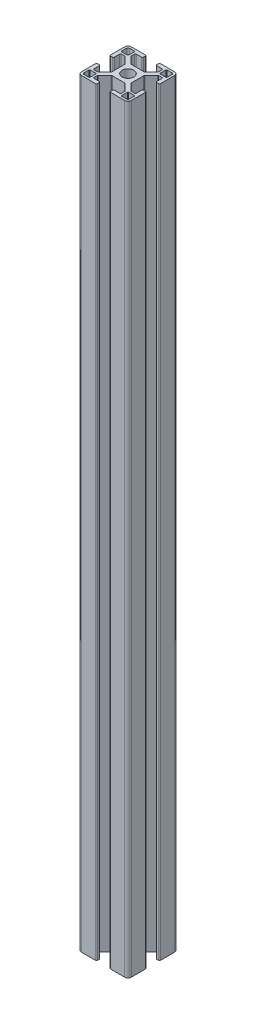
SolidWorks part; units mm, degrees
ref_plane "Front Plane" through (0, 0, 0) normal (0, 0, 1) x (1, 0, 0)
ref_plane "Top Plane" through (0, 0, 0) normal (0, 1, 0) x (1, 0, 0)
ref_plane "Right Plane" through (0, 0, 0) normal (1, 0, 0) x (0, 0, -1)
sketch "Sketch1" plane through (0, 0, 0) normal (0, 1, 0) x (1, 0, 0)
  line L0 (3.9799, -2.4733) -> (3.1981, -1.4942) construction
  line L1 (1.4942, -3.1981) -> (2.4733, -3.9799) construction
  line L2 (-2.4733, -3.9799) -> (-1.4942, -3.1981) construction
  line L3 (-3.1981, -1.4942) -> (-3.9799, -2.4733) construction
  line L4 (-3.9799, 2.4733) -> (-3.1981, 1.4942) construction
  line L5 (-1.4942, 3.1981) -> (-2.4733, 3.9799) construction
  line L6 (2.4733, 3.9799) -> (1.4942, 3.1981) construction
  line L7 (3.1981, 1.4942) -> (3.9799, 2.4733) construction
  line L8 (-12.6999, -13.6999) -> (-9.881, -13.6999)
  line L9 (-13.6999, -9.881) -> (-13.6999, -12.6999)
  line L10 (-9.88, -9.5) -> (-13.3189, -9.5)
  line L11 (-9.5, -13.3189) -> (-9.5, -9.88)
  line L12 (13.6999, -12.6999) -> (13.6999, -9.881)
  line L13 (9.881, -13.6999) -> (12.6999, -13.6999)
  line L14 (9.5, -9.88) -> (9.5, -13.3189)
  line L15 (13.3189, -9.5) -> (9.88, -9.5)
  line L16 (9.88, 9.5) -> (13.3189, 9.5)
  line L17 (9.5, 13.3189) -> (9.5, 9.88)
  line L18 (12.6999, 13.6999) -> (9.881, 13.6999)
  line L19 (13.6999, 9.881) -> (13.6999, 12.6999)
  line L20 (-13.6999, 12.6999) -> (-13.6999, 9.881)
  line L21 (-9.881, 13.6999) -> (-12.6999, 13.6999)
  line L22 (-9.5, 9.88) -> (-9.5, 13.3189)
  line L23 (-13.3189, 9.5) -> (-9.88, 9.5)
  line L24 (14.4999, -4) -> (13.2425, -4)
  line L25 (12.7425, -4.5) -> (12.7425, -7.7325)
  line L26 (12.2428, -8.25) -> (10.2602, -8.25)
  line L27 (9.9066, -8.1035) -> (5.9811, -4.178)
  line L28 (5.8347, -3.8245) -> (5.8347, -1.0125)
  line L29 (5.8347, -1.0125) -> (5.3247, -0.0625) construction
  line L30 (5.3247, -0.0625) -> (5.8347, 0.8875) construction
  line L31 (5.8347, 0.8875) -> (5.8347, 3.8245)
  line L32 (5.9811, 4.178) -> (9.9066, 8.1035)
  line L33 (10.2602, 8.25) -> (12.2428, 8.25)
  line L34 (12.7425, 7.7325) -> (12.7425, 4.5)
  line L35 (13.2425, 4) -> (14.4999, 4)
  line L36 (14.9999, 4.5) -> (14.9999, 12.9999)
  line L37 (12.9999, 14.9999) -> (4.5, 14.9999)
  line L38 (4, 14.4999) -> (4, 13.2425)
  line L39 (4.5, 12.7425) -> (7.7325, 12.7425)
  line L40 (8.25, 12.2428) -> (8.25, 10.2602)
  line L41 (8.1035, 9.9066) -> (4.178, 5.9811)
  line L42 (3.8245, 5.8347) -> (0.95, 5.8347)
  line L43 (0.95, 5.8347) -> (0, 5.3247) construction
  line L44 (0, 5.3247) -> (-0.95, 5.8347) construction
  line L45 (-0.95, 5.8347) -> (-3.8245, 5.8347)
  line L46 (-4.178, 5.9811) -> (-8.1035, 9.9066)
  line L47 (-8.25, 10.2602) -> (-8.25, 12.2428)
  line L48 (-7.7325, 12.7425) -> (-4.5, 12.7425)
  line L49 (-4, 13.2425) -> (-4, 14.4999)
  line L50 (-4.5, 14.9999) -> (-12.9999, 14.9999)
  line L51 (-14.9999, 12.9999) -> (-14.9999, 4.5)
  line L52 (-14.4999, 4) -> (-13.2425, 4)
  line L53 (-12.7425, 4.5) -> (-12.7425, 7.7325)
  line L54 (-12.2428, 8.25) -> (-10.2602, 8.25)
  line L55 (-9.9066, 8.1035) -> (-5.9811, 4.178)
  line L56 (-5.8347, 3.8245) -> (-5.8347, 0.8875)
  line L57 (-5.8347, 0.8875) -> (-5.3247, -0.0625) construction
  line L58 (-5.3247, -0.0625) -> (-5.8347, -1.0125) construction
  line L59 (-5.8347, -1.0125) -> (-5.8347, -3.8245)
  line L60 (-5.9811, -4.178) -> (-9.9066, -8.1035)
  line L61 (-10.2602, -8.25) -> (-12.2428, -8.25)
  line L62 (-12.7425, -7.7325) -> (-12.7425, -4.5)
  line L63 (-13.2425, -4) -> (-14.4999, -4)
  line L64 (-14.9999, -4.5) -> (-14.9999, -12.9999)
  line L65 (-12.9999, -14.9999) -> (-4.5, -14.9999)
  line L66 (-4, -14.4999) -> (-4, -13.2425)
  line L67 (-4.5, -12.7425) -> (-7.7325, -12.7425)
  line L68 (-8.25, -12.2428) -> (-8.25, -10.2602)
  line L69 (-8.1035, -9.9066) -> (-4.178, -5.9811)
  line L70 (-3.8245, -5.8347) -> (-0.95, -5.8347)
  line L71 (-0.95, -5.8347) -> (0, -5.3247) construction
  line L72 (0, -5.3247) -> (0.95, -5.8347) construction
  line L73 (0.95, -5.8347) -> (3.8245, -5.8347)
  line L74 (4.178, -5.9811) -> (8.1035, -9.9066)
  line L75 (8.25, -10.2602) -> (8.25, -12.2428)
  line L76 (7.7325, -12.7425) -> (4.5, -12.7425)
  line L77 (4, -13.2425) -> (4, -14.4999)
  line L78 (4.5, -14.9999) -> (12.9999, -14.9999)
  line L79 (14.9999, -12.9999) -> (14.9999, -4.5)
  line L80 (-5.8347, -1.0125) -> (-5.8347, 0.8875)
  line L81 (-0.95, 5.8347) -> (0.95, 5.8347)
  line L82 (5.8347, 0.8875) -> (5.8347, -1.0125)
  line L83 (-0.95, -5.8347) -> (0.95, -5.8347)
  arc A0 (2.4733, -3.9799) -> (3.9799, -2.4733) centre (3.1422, -3.1422) ccw construction
  arc A1 (-1.4942, -3.1981) -> (1.4942, -3.1981) centre (0, 0) ccw construction
  arc A2 (-3.9799, -2.4733) -> (-2.4733, -3.9799) centre (-3.1422, -3.1422) ccw construction
  arc A3 (-3.1981, 1.4942) -> (-3.1981, -1.4942) centre (0, 0) ccw construction
  arc A4 (-2.4733, 3.9799) -> (-3.9799, 2.4733) centre (-3.1422, 3.1422) ccw construction
  arc A5 (1.4942, 3.1981) -> (-1.4942, 3.1981) centre (0, 0) ccw construction
  arc A6 (3.9799, 2.4733) -> (2.4733, 3.9799) centre (3.1422, 3.1422) ccw construction
  arc A7 (3.1981, -1.4942) -> (3.1981, 1.4942) centre (0, 0) ccw construction
  arc A8 (-13.6999, -12.6999) -> (-12.6999, -13.6999) centre (-12.6999, -12.6999) ccw
  arc A9 (-13.3189, -9.5) -> (-13.6999, -9.881) centre (-13.3189, -9.881) ccw
  arc A10 (-9.5, -9.88) -> (-9.88, -9.5) centre (-9.88, -9.88) ccw
  arc A11 (-9.881, -13.6999) -> (-9.5, -13.3189) centre (-9.881, -13.3189) ccw
  arc A12 (12.6999, -13.6999) -> (13.6999, -12.6999) centre (12.6999, -12.6999) ccw
  arc A13 (9.5, -13.3189) -> (9.881, -13.6999) centre (9.881, -13.3189) ccw
  arc A14 (9.88, -9.5) -> (9.5, -9.88) centre (9.88, -9.88) ccw
  arc A15 (13.6999, -9.881) -> (13.3189, -9.5) centre (13.3189, -9.881) ccw
  arc A16 (9.5, 9.88) -> (9.88, 9.5) centre (9.88, 9.88) ccw
  arc A17 (9.881, 13.6999) -> (9.5, 13.3189) centre (9.881, 13.3189) ccw
  arc A18 (13.6999, 12.6999) -> (12.6999, 13.6999) centre (12.6999, 12.6999) ccw
  arc A19 (13.3189, 9.5) -> (13.6999, 9.881) centre (13.3189, 9.881) ccw
  arc A20 (14.9999, -4.5) -> (14.4999, -4) centre (14.4999, -4.5) ccw
  arc A21 (13.2425, -4) -> (12.7425, -4.5) centre (13.2425, -4.5) ccw
  arc A22 (12.2428, -8.25) -> (12.7425, -7.7325) centre (12.2428, -7.75) ccw
  arc A23 (9.9066, -8.1035) -> (10.2602, -8.25) centre (10.2602, -7.75) ccw
  arc A24 (5.8347, -3.8245) -> (5.9811, -4.178) centre (6.3347, -3.8245) ccw
  arc A25 (5.9811, 4.178) -> (5.8347, 3.8245) centre (6.3347, 3.8245) ccw
  arc A26 (10.2602, 8.25) -> (9.9066, 8.1035) centre (10.2602, 7.75) ccw
  arc A27 (12.7425, 7.7325) -> (12.2428, 8.25) centre (12.2428, 7.75) ccw
  arc A28 (12.7425, 4.5) -> (13.2425, 4) centre (13.2425, 4.5) ccw
  arc A29 (14.4999, 4) -> (14.9999, 4.5) centre (14.4999, 4.5) ccw
  arc A30 (14.9999, 12.9999) -> (12.9999, 14.9999) centre (12.9999, 12.9999) ccw
  arc A31 (4.5, 14.9999) -> (4, 14.4999) centre (4.5, 14.4999) ccw
  arc A32 (4, 13.2425) -> (4.5, 12.7425) centre (4.5, 13.2425) ccw
  arc A33 (8.25, 12.2428) -> (7.7325, 12.7425) centre (7.75, 12.2428) ccw
  arc A34 (8.1035, 9.9066) -> (8.25, 10.2602) centre (7.75, 10.2602) ccw
  arc A35 (3.8245, 5.8347) -> (4.178, 5.9811) centre (3.8245, 6.3347) ccw
  arc A36 (-4.178, 5.9811) -> (-3.8245, 5.8347) centre (-3.8245, 6.3347) ccw
  arc A37 (-8.25, 10.2602) -> (-8.1035, 9.9066) centre (-7.75, 10.2602) ccw
  arc A38 (-7.7325, 12.7425) -> (-8.25, 12.2428) centre (-7.75, 12.2428) ccw
  arc A39 (-4.5, 12.7425) -> (-4, 13.2425) centre (-4.5, 13.2425) ccw
  arc A40 (-4, 14.4999) -> (-4.5, 14.9999) centre (-4.5, 14.4999) ccw
  arc A41 (-12.9999, 14.9999) -> (-14.9999, 12.9999) centre (-12.9999, 12.9999) ccw
  arc A42 (-14.9999, 4.5) -> (-14.4999, 4) centre (-14.4999, 4.5) ccw
  arc A43 (-13.2425, 4) -> (-12.7425, 4.5) centre (-13.2425, 4.5) ccw
  arc A44 (-12.2428, 8.25) -> (-12.7425, 7.7325) centre (-12.2428, 7.75) ccw
  arc A45 (-9.9066, 8.1035) -> (-10.2602, 8.25) centre (-10.2602, 7.75) ccw
  arc A46 (-5.8347, 3.8245) -> (-5.9811, 4.178) centre (-6.3347, 3.8245) ccw
  arc A47 (-5.9811, -4.178) -> (-5.8347, -3.8245) centre (-6.3347, -3.8245) ccw
  arc A48 (-10.2602, -8.25) -> (-9.9066, -8.1035) centre (-10.2602, -7.75) ccw
  arc A49 (-12.7425, -7.7325) -> (-12.2428, -8.25) centre (-12.2428, -7.75) ccw
  arc A50 (-12.7425, -4.5) -> (-13.2425, -4) centre (-13.2425, -4.5) ccw
  arc A51 (-14.4999, -4) -> (-14.9999, -4.5) centre (-14.4999, -4.5) ccw
  arc A52 (-14.9999, -12.9999) -> (-12.9999, -14.9999) centre (-12.9999, -12.9999) ccw
  arc A53 (-4.5, -14.9999) -> (-4, -14.4999) centre (-4.5, -14.4999) ccw
  arc A54 (-4, -13.2425) -> (-4.5, -12.7425) centre (-4.5, -13.2425) ccw
  arc A55 (-8.25, -12.2428) -> (-7.7325, -12.7425) centre (-7.75, -12.2428) ccw
  arc A56 (-8.1035, -9.9066) -> (-8.25, -10.2602) centre (-7.75, -10.2602) ccw
  arc A57 (-3.8245, -5.8347) -> (-4.178, -5.9811) centre (-3.8245, -6.3347) ccw
  arc A58 (4.178, -5.9811) -> (3.8245, -5.8347) centre (3.8245, -6.3347) ccw
  arc A59 (8.25, -10.2602) -> (8.1035, -9.9066) centre (7.75, -10.2602) ccw
  arc A60 (7.7325, -12.7425) -> (8.25, -12.2428) centre (7.75, -12.2428) ccw
  arc A61 (4.5, -12.7425) -> (4, -13.2425) centre (4.5, -13.2425) ccw
  arc A62 (4, -14.4999) -> (4.5, -14.9999) centre (4.5, -14.4999) ccw
  arc A63 (12.9999, -14.9999) -> (14.9999, -12.9999) centre (12.9999, -12.9999) ccw
  arc A64 (-12.6999, 13.6999) -> (-13.6999, 12.6999) centre (-12.6999, 12.6999) ccw
  arc A65 (-9.5, 13.3189) -> (-9.881, 13.6999) centre (-9.881, 13.3189) ccw
  arc A66 (-9.88, 9.5) -> (-9.5, 9.88) centre (-9.88, 9.88) ccw
  arc A67 (-13.6999, 9.881) -> (-13.3189, 9.5) centre (-13.3189, 9.881) ccw
  circle A68 centre (0, 0) radius 3.53
extrude "Boss-Extrude1" add sketch "Sketch1" along normal mid plane 457.2
